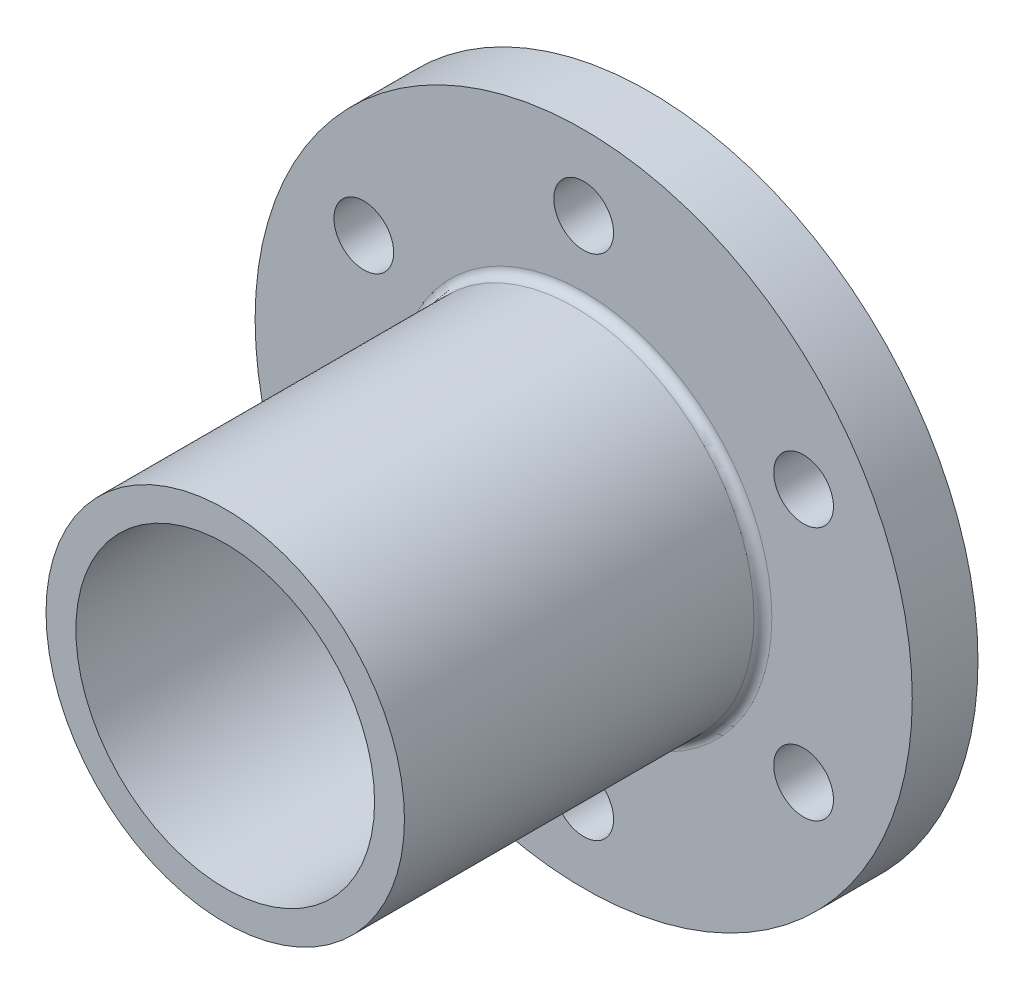
SolidWorks part; units mm, degrees
ref_plane "Front Plane" through (0, 0, 0) normal (0, 0, 1) x (1, 0, 0)
ref_plane "Top Plane" through (0, 0, 0) normal (0, 1, 0) x (1, 0, 0)
ref_plane "Right Plane" through (0, 0, 0) normal (1, 0, 0) x (0, 0, -1)
sketch "Sketch1" plane through (0, 0, 0) normal (0, 0, 1) x (1, 0, 0)
  circle A0 centre (0, 0) radius 110
  dimension "D1" = 220
extrude "Boss-Extrude1" add sketch "Sketch1" along normal blind 22
sketch "Sketch2" plane through (0, 0, 22) normal (0, 0, 1) x (1, 0, 0)
  circle A0 centre (0, 0) radius 60
  dimension "D1" = 120
extrude "Boss-Extrude2" add sketch "Sketch2" along normal blind 120
sketch "Sketch3" plane through (0, 0, 142) normal (0, 0, 1) x (1, 0, 0)
  circle A0 centre (0, 0) radius 50
  dimension "D1" = 100
extrude "Cut-Extrude1" cut sketch "Sketch3" against normal through all
sketch "Sketch4" plane through (0, 0, 22) normal (0, 0, 1) x (1, 0, 0)
  circle A0 centre (0, 85) radius 10
  circle A1 centre (73.6122, 42.5) radius 10
  circle A2 centre (73.6122, -42.5) radius 10
  circle A3 centre (0, -85) radius 10
  circle A4 centre (-73.6122, -42.5) radius 10
  circle A5 centre (-73.6122, 42.5) radius 10
  point P16 (0, 0)
  dimension "D1" = 20
  dimension "D2" = 85
  dimension "D3" = 6
extrude "Cut-Extrude2" cut sketch "Sketch4" against normal through all
fillet "Fillet1" radius 3 1 edges at (60, 0, 22)
